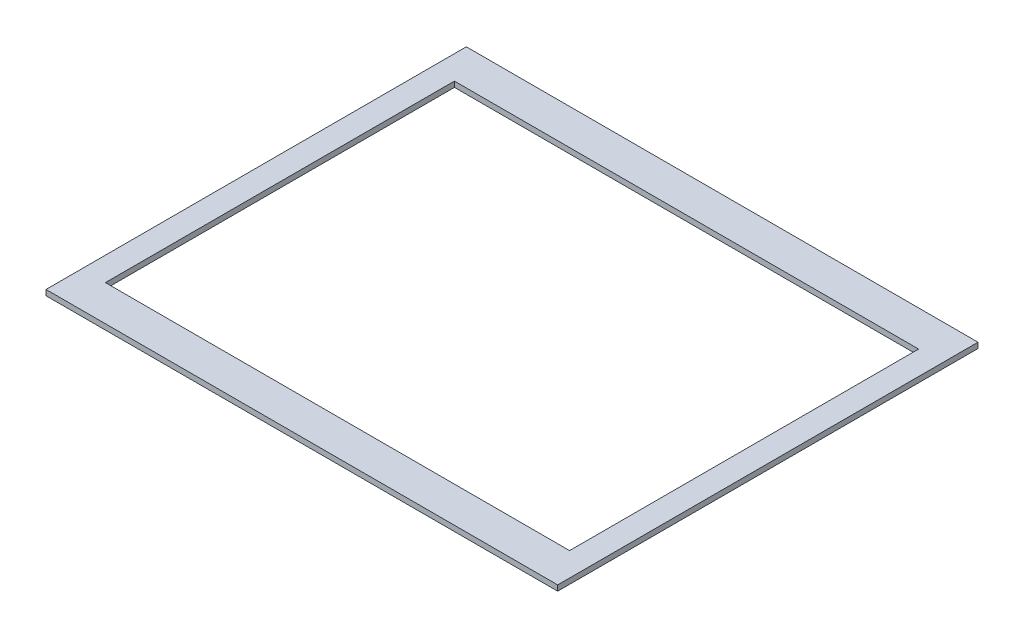
SolidWorks part; units mm, degrees
ref_plane "Front Plane" through (0, 0, 0) normal (0, 0, 1) x (1, 0, 0)
ref_plane "Top Plane" through (0, 0, 0) normal (0, 1, 0) x (1, 0, 0)
ref_plane "Right Plane" through (0, 0, 0) normal (1, 0, 0) x (0, 0, -1)
sketch "Sketch1" plane through (0, 0, 0) normal (0, 1, 0) x (1, 0, 0)
  line L0 (140, 230) -> (140, 210.5) construction
  line L1 (0, 0) -> (280, 0)
  line L2 (0, 0) -> (0, 230)
  line L3 (0, 230) -> (280, 230)
  line L4 (280, 0) -> (280, 230)
  line L5 (280, 210.5) -> (267, 210.5) construction
  line L6 (140, 0) -> (140, 19.5) construction
  line L7 (0, 19.5) -> (13, 19.5) construction
  line L9 (13, 19.5) -> (267, 19.5)
  line L10 (13, 19.5) -> (13, 210.5)
  line L11 (13, 210.5) -> (267, 210.5)
  line L12 (267, 19.5) -> (267, 210.5)
  dimension "D1" = 280
  dimension "D2" = 230
  dimension "D3" = 19.5
  dimension "D4" = 13
  dimension "D5" = 19.5
  dimension "D6" = 13
extrude "Boss-Extrude1" add sketch "Sketch1" along normal blind 3
